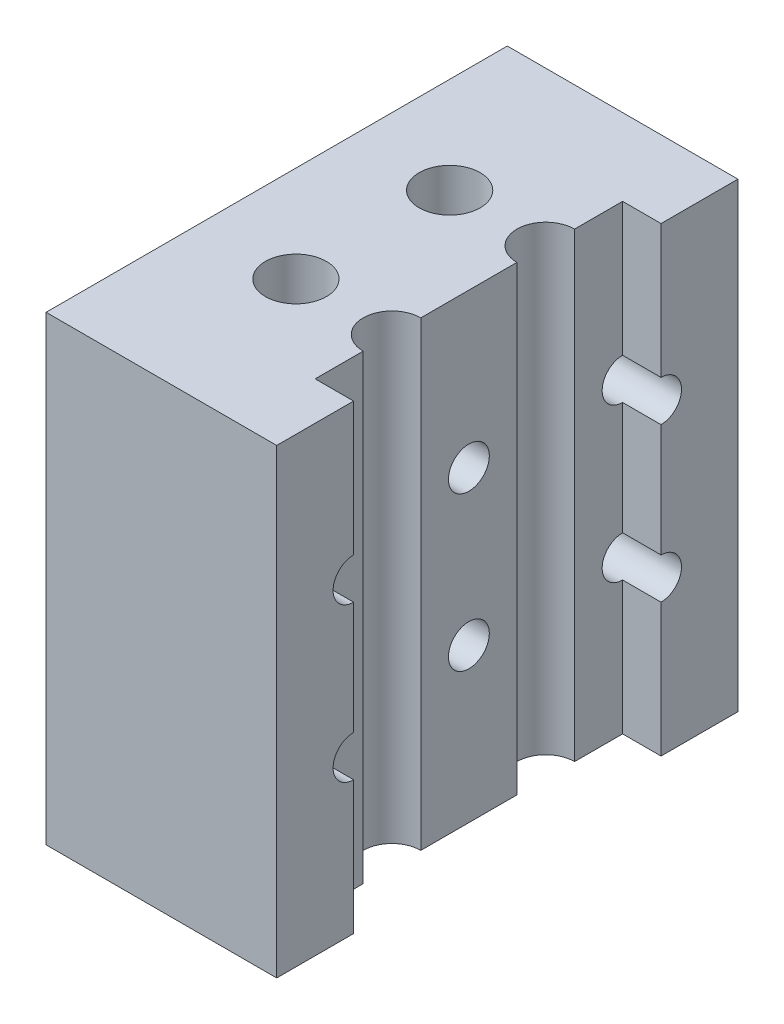
SolidWorks part; units mm, degrees
material "Copper"
ref_plane "Front Plane" through (0, 0, 0) normal (0, 0, 1) x (1, 0, 0)
ref_plane "Top Plane" through (0, 0, 0) normal (0, 1, 0) x (1, 0, 0)
ref_plane "Right Plane" through (0, 0, 0) normal (1, 0, 0) x (0, 0, -1)
sketch "Sketch1" plane through (0, 0, 0) normal (0, 1, 0) x (1, 0, 0)
  line L1 (-38.1, 38.1) -> (0, 38.1)
  line L2 (-38.1, 38.1) -> (-38.1, -38.1)
  line L3 (-38.1, -38.1) -> (0, -38.1)
  line L4 (0, 38.1) -> (0, -38.1)
  dimension "D1" = 38.1
  dimension "D2" = 76.2
  dimension "D4" = 38.1
extrude "Boss-Extrude1" add sketch "Sketch1" along normal blind 76.2
sketch "Sketch2" plane through (0, 76.2, 0) normal (0, 1, 0) x (1, 0, 0)
  line L1 (0, -38.1) -> (0, 38.1) construction
  line L2 (0, 25.4) -> (-6.35, 25.4)
  line L3 (0, 25.4) -> (0, -25.4)
  line L4 (0, -25.4) -> (-6.35, -25.4)
  line L5 (-6.35, 25.4) -> (-6.35, -25.4)
  dimension "D1" = 6.35
  dimension "D2" = 50.8
  dimension "D3" = 25.4
extrude "Cut-Extrude1" cut sketch "Sketch2" against normal through all
hole_wizard "1/4 Clearance Hole1" positions "Sketch4" profile "Sketch3" hole size "1/4" standard "ANSI Inch" end condition through all
sketch "Sketch4" plane through (0, 0, 0) normal (1, 0, 0) x (0, 0, -1)
  point P0 (0, 50.8)
  point P2 (0, 25.4)
  point P4 (-25.4, 25.4)
  point P6 (-25.4, 50.8)
  point P8 (25.4, 50.8)
  point P10 (25.4, 25.4)
sketch "Sketch3" plane through (0, 50.8, 0) normal (0, 1, 0) x (0, 0, -1)
  line L0 (0, 0) -> (0, 38.1)
  line L1 (0, 38.1) -> (3.3782, 38.1)
  line L2 (3.3782, 38.1) -> (3.3782, 0)
  line L5 (3.3782, 0) -> (0, 0)
  line L11 (0, -6.35) -> (0, 107.95) construction
  dimension "Thru Hole Dia." = 6.7564
  dimension "Thru Hole Depth" = 38.1
hole_wizard "3/8 Clearance Hole1" positions "Sketch6" profile "Sketch5" hole size "3/8" standard "ANSI Inch" end condition through all
sketch "Sketch6" plane through (0, 76.2, 0) normal (0, 1, 0) x (1, 0, 0)
  point P0 (-22.225, -12.7)
  point P2 (-22.225, 12.7)
sketch "Sketch5" plane through (-22.225, 76.2, 12.7) normal (1, 0, 0) x (0, 0, 1)
  line L0 (0, 0) -> (0, 76.2)
  line L1 (0, 76.2) -> (5.0419, 76.2)
  line L2 (5.0419, 76.2) -> (5.0419, 0)
  line L5 (5.0419, 0) -> (0, 0)
  line L11 (0, -6.35) -> (0, 107.95) construction
  dimension "Thru Hole Dia." = 10.0838
  dimension "Thru Hole Depth" = 76.2
sketch "Sketch7" plane through (0, 76.2, 0) normal (0, 1, 0) x (1, 0, 0)
  line L0 (-6.35, 25.4) -> (-6.35, -25.4) construction
  line L1 (-6.35, 25.4) -> (-6.35, -25.4) construction
  circle A0 centre (-6.35, 12.7) radius 4.7625
  circle A1 centre (-6.35, -12.7) radius 4.7625
  point P6 (-6.35, 0)
  point P9 (-6.35, 0)
  dimension "D1" = 9.525
  dimension "D2" = 12.7
  dimension "D3" = 12.7
extrude "Cut-Extrude2" cut sketch "Sketch7" against normal through all
